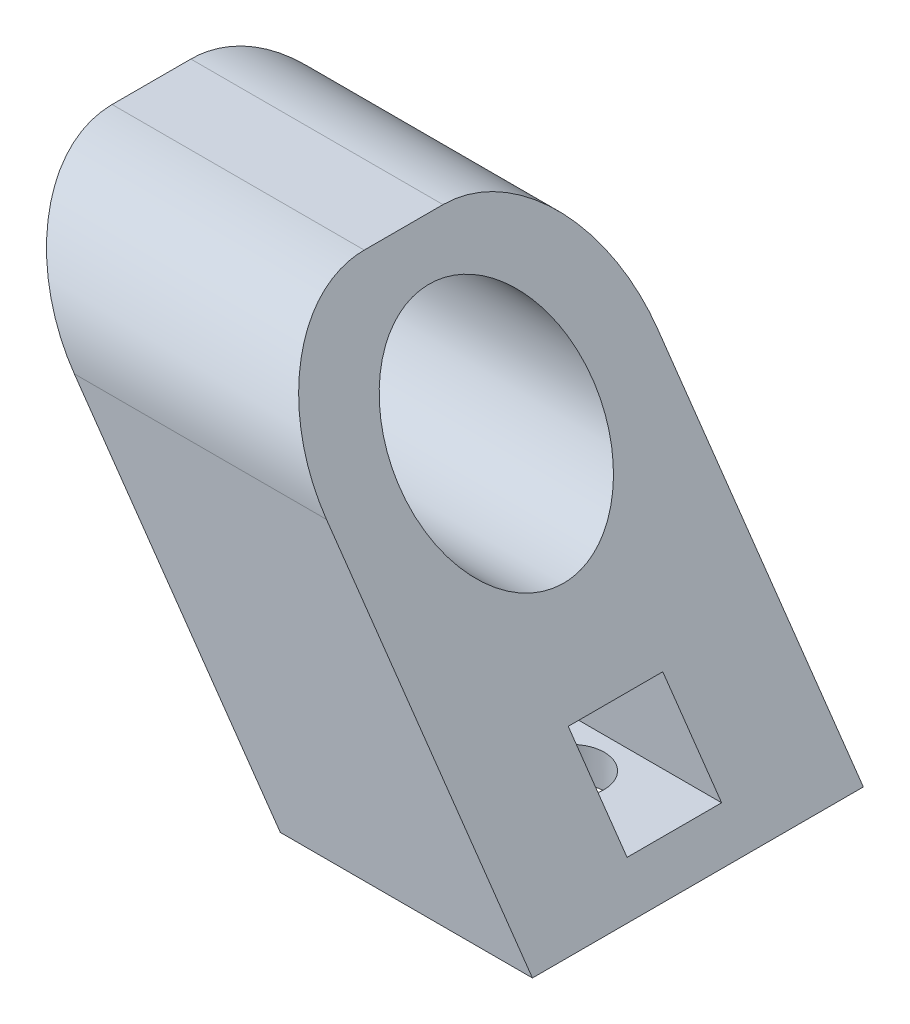
SolidWorks part; units mm, degrees
ref_plane "Front Plane" through (0, 0, 0) normal (0, 0, 1) x (1, 0, 0)
ref_plane "Top Plane" through (0, 0, 0) normal (0, 1, 0) x (1, 0, 0)
ref_plane "Right Plane" through (0, 0, 0) normal (1, 0, 0) x (0, 0, -1)
sketch "Sketch2" plane through (0, 0, 0) normal (0, 0, 1) x (1, 0, 0)
  line L0 (-28.9362, 20) -> (15.527, -43.5)
  line L1 (15.527, -43.5) -> (53.627, -43.5)
  line L2 (53.627, -43.5) -> (9.1638, 20)
  line L3 (9.1638, 20) -> (-28.9362, 20)
  line L4 (7.5343, -37.9446) -> (46.5543, -37.9446) construction
  line L5 (46.5543, -37.9446) -> (62.6682, -60.8431) construction
  line L6 (62.6682, -60.8431) -> (7.5343, -37.9446) construction
  dimension "D1" = 59.7
  dimension "D2" = 39.02
  dimension "D3" = 28
  dimension "D4" = 125.134
  dimension "D5" = 125
  dimension "D6" = 38.1
  dimension "D7" = 63.5
  dimension "D8" = 20
extrude "Boss-Extrude1" add sketch "Sketch2" along normal mid plane 50
fillet "Fillet1" radius 19.05 2 edges at (-9.8862, 20, -25) (-9.8862, 20, 25)
sketch "Sketch3" plane through (0, 0, 0) normal (1, 0, 0) x (0, 0, -1)
  line L0 (-25, -43.5) -> (25, -43.5) construction
  line L1 (-7.1437, -25.72) -> (7.1438, -25.72)
  line L2 (-7.1437, -25.72) -> (-7.1437, -38.42)
  line L3 (-7.1437, -38.42) -> (7.1438, -38.42)
  line L4 (7.1438, -25.72) -> (7.1438, -38.42)
  line L5 (-7.1437, -25.72) -> (7.1438, -38.42) construction
  line L6 (-7.1437, -38.42) -> (7.1438, -25.72) construction
  line L7 (0, 0) -> (0, -76.5505) construction
  circle A0 centre (0, 0) radius 14.5
  point P3 (0, -32.07)
  point P8 (0, 0)
  dimension "D1" = 29
  dimension "D2" = 5.08
  dimension "D3" = 12.7
  dimension "D4" = 14.2875
extrude "Cut-Extrude1" cut sketch "Sketch3" against normal through all both and the other way through all
sketch "Sketch5" plane through (0, -43.5, 0) normal (0, -1, 0) x (1, 0, 0)
  line L2 (34.577, 14.228) -> (34.577, -15.2961) construction
  line L3 (53.627, 25) -> (53.627, -25) construction
  line L4 (15.527, 25) -> (15.527, -25) construction
  circle A0 centre (34.577, 0) radius 4.8895
  point P2 (0, 0)
  point P9 (0, 0)
  dimension "D1" = 9.779
extrude "Cut-Extrude2" cut sketch "Sketch5" against normal blind 12.7
equation "\"D4@Sketch3\"=9/16"
